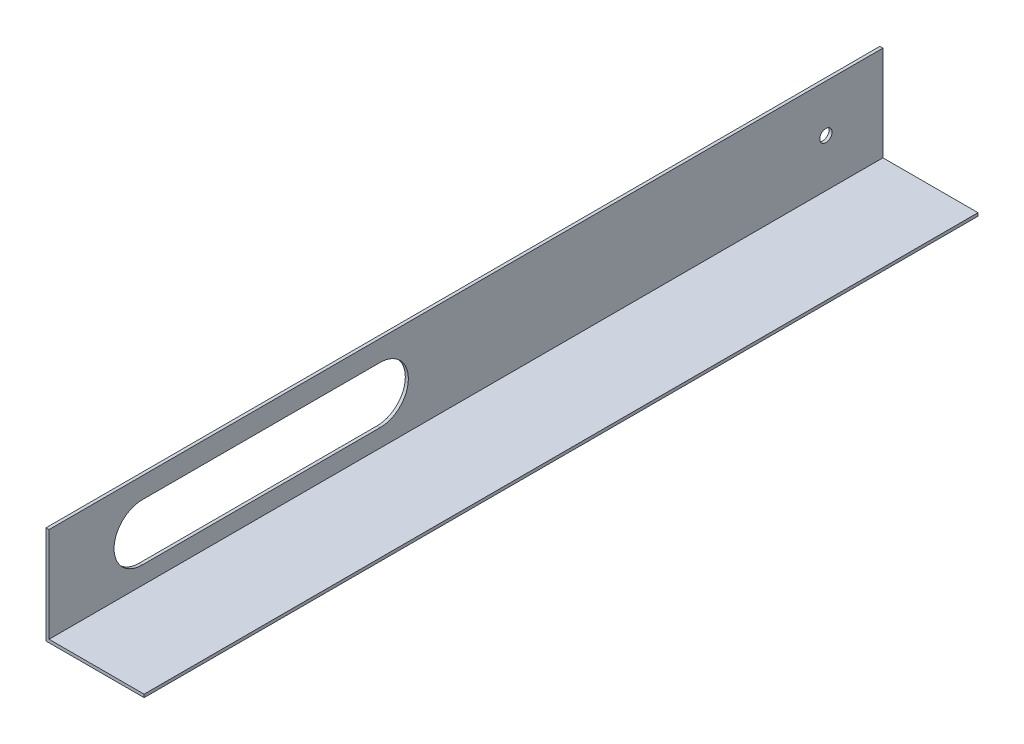
SolidWorks part; units mm, degrees
ref_plane "Front Plane" through (0, 0, 0) normal (0, 0, 1) x (1, 0, 0)
ref_plane "Top Plane" through (0, 0, 0) normal (0, 1, 0) x (1, 0, 0)
ref_plane "Right Plane" through (0, 0, 0) normal (1, 0, 0) x (0, 0, -1)
sketch "Sketch3" plane through (0, 0, 0) normal (0, 0, 1) x (1, 0, 0)
  line L0 (0, 0) -> (0, 49.2125)
  line L1 (0, 49.2125) -> (-1.5875, 49.2125)
  line L2 (-1.5875, 49.2125) -> (-1.5875, -1.5875)
  line L3 (-1.5875, -1.5875) -> (49.2125, -1.5875)
  line L4 (49.2125, -1.5875) -> (49.2125, 0)
  line L5 (49.2125, 0) -> (0, 0)
  dimension "D1" = 1.5875
  dimension "D2" = 1.5875
  dimension "D3" = 50.8
  dimension "D4" = 50.8
extrude "Boss-Extrude2" add sketch "Sketch3" along normal blind 431.8
sketch "Sketch6" plane through (0, 0, 0) normal (1, 0, 0) x (0, 0, -1)
  line L0 (-383.54, 23.8125) -> (-260.35, 23.8125) construction
  line L1 (-383.54, 38.4175) -> (-260.35, 38.4175)
  line L2 (-383.54, 9.2075) -> (-260.35, 9.2075)
  line L3 (-431.8, 0) -> (-431.8, 49.2125) construction
  line L4 (-431.8, 49.2125) -> (0, 49.2125) construction
  arc A0 (-383.54, 38.4175) -> (-383.54, 9.2075) centre (-383.54, 23.8125) ccw
  arc A1 (-260.35, 9.2075) -> (-260.35, 38.4175) centre (-260.35, 23.8125) ccw
  point P2 (-321.945, 23.8125)
  dimension "D1" = 29.21
  dimension "D2" = 123.19
  dimension "D3" = 48.26
  dimension "D4" = 25.4
extrude "Cut-Extrude3" cut sketch "Sketch6" against normal blind 127
sketch "Sketch7" plane through (0, 0, 0) normal (1, 0, 0) x (0, 0, -1)
  circle A0 centre (-29.5388, 24.7736) radius 3.175
  dimension "D1" = 6.35
extrude "Cut-Extrude4" cut sketch "Sketch7" against normal blind 127
